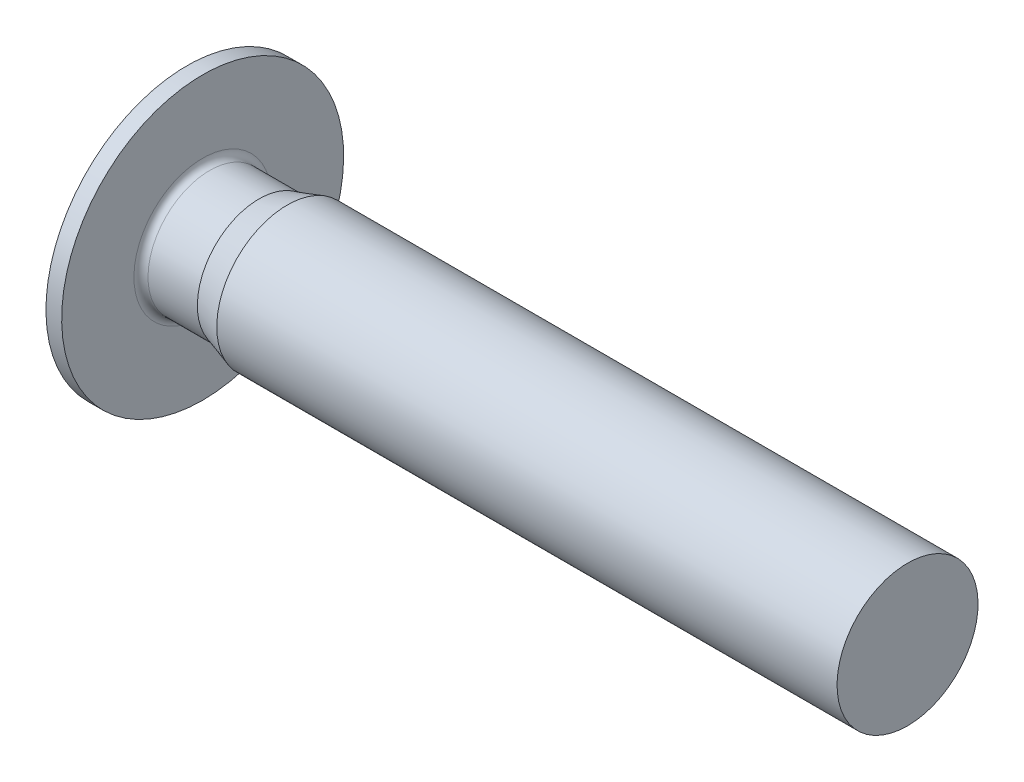
SolidWorks part; units mm, degrees
material "SCM435"
ref_plane "Front Plane" through (0, 0, 0) normal (0, 0, 1) x (1, 0, 0)
ref_plane "Top Plane" through (0, 0, 0) normal (0, 1, 0) x (1, 0, 0)
ref_plane "Right Plane" through (0, 0, 0) normal (1, 0, 0) x (0, 0, -1)
sketch "Sketch1" plane through (0, 0, 0) normal (0, 0, 1) x (1, 0, 0)
  line L0 (-0.5, 0) -> (10, 0) construction
  line L1 (-0.5, 0) -> (-0.5, 1.52)
  line L2 (-0.2229, 2) -> (0, 2)
  line L3 (0, 2) -> (0, 0.875)
  line L4 (1.2, 1) -> (10, 1)
  line L5 (10, 1) -> (10, 0)
  line L6 (10, 0) -> (-0.5, 0)
  line L7 (1.2, 1) -> (0.8, 0.875)
  line L8 (0.8, 0.875) -> (0, 0.875)
  line L9 (-0.2229, 2) -> (-0.5, 1.52)
  line L10 (-0.5, 0) -> (10, 0) construction
  dimension "A" = 4
  dimension "M" = 2
  dimension "L" = 10
  dimension "E" = 0.5
  dimension "FIX_1" = 30
  dimension "MSM_1" = 3.04
  dimension "MSM_2" = 1.75
  dimension "MSM_3" = 0.4
  dimension "E_s" = 1.2
revolve "Revolve1" add sketch "Sketch1" angle 360 about L0
cosmetic thread "Thread1" parameters "ATL_1"=8.8, "ATD"=1.567
fillet "Fillet1" radius 0.1 1 edges at (0, -0.875, 0)
sketch "Sketch2" plane through (-0.5, 0, 0) normal (-1, 0, 0) x (0, 0, 1)
  line L1 (0, 0.7506) -> (-0.65, 0.3753)
  line L2 (-0.65, 0.3753) -> (-0.65, -0.3753)
  line L3 (-0.65, -0.3753) -> (0, -0.7506)
  line L4 (0, -0.7506) -> (0.65, -0.3753)
  line L5 (0.65, -0.3753) -> (0.65, 0.3753)
  line L6 (0.65, 0.3753) -> (0, 0.7506)
  circle A0 centre (0, 0) radius 0.65 construction
  dimension "B" = 1.3
extrude "Cut-Extrude1" cut sketch "Sketch2" against normal blind 1.2
sketch "Sketch3" plane through (0, 0, 0) normal (0, 0, 1) x (1, 0, 0)
  line L0 (0.7, 0) -> (1.0906, 0) construction
  line L1 (0.7, 0) -> (0.7, 0.65)
  line L2 (0.7, 0.65) -> (1.0906, 0)
  line L3 (1.0906, 0) -> (0.7, 0)
  line L5 (0.7, 0.3753) -> (0.7, -0.3753) construction
  dimension "FIX_3" = 59
  dimension "B" = 1.3
revolve "Cut-Revolve1" cut sketch "Sketch3" angle 360 about L0
equation "\"ATL_1@Thread1\" = \"L@Sketch1\" - \"E_s@Sketch1\""
